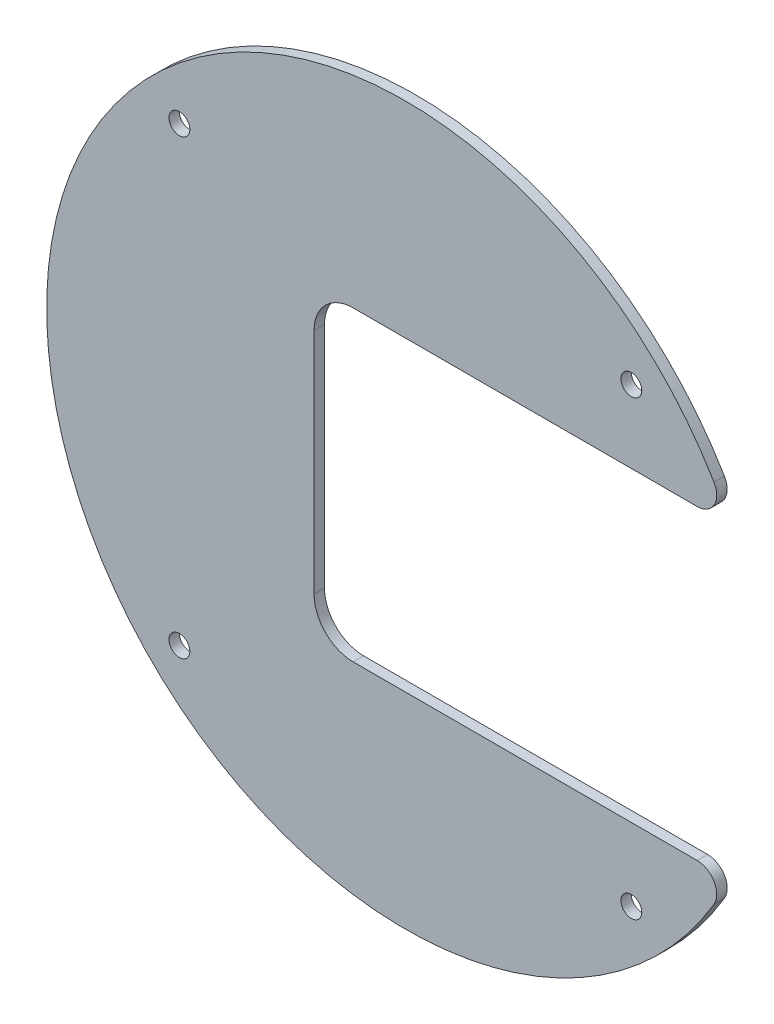
SolidWorks part; units mm, degrees
ref_plane "Front Plane" through (0, 0, 0) normal (0, 0, 1) x (1, 0, 0)
ref_plane "Top Plane" through (0, 0, 0) normal (0, 1, 0) x (1, 0, 0)
ref_plane "Right Plane" through (0, 0, 0) normal (1, 0, 0) x (0, 0, -1)
sketch "草圖1" plane through (0, 0, 0) normal (0, 0, 1) x (1, 0, 0)
  line L0 (49.7268, -23.5) -> (-14, -23.5)
  line L1 (-14, -23.5) -> (-14, 23.5)
  line L2 (-14, 23.5) -> (49.7268, 23.5)
  arc A0 (49.7268, 23.5) -> (49.7268, -23.5) centre (0, 0) ccw
  circle A1 centre (34.6482, 34.6482) radius 1.6
  circle A2 centre (-34.6482, 34.6482) radius 1.6
  circle A3 centre (-34.6482, -34.6482) radius 1.6
  circle A4 centre (34.6482, -34.6482) radius 1.6
extrude "填料-伸長1" add sketch "草圖1" along normal blind 1.6
fillet "圓角1" radius 6 2 edges at (-14, 23.5, 0.8) (-14, -23.5, 0.8)
fillet "圓角2" radius 3 2 edges at (49.7268, 23.5, 0.8) (49.7268, -23.5, 0.8)
